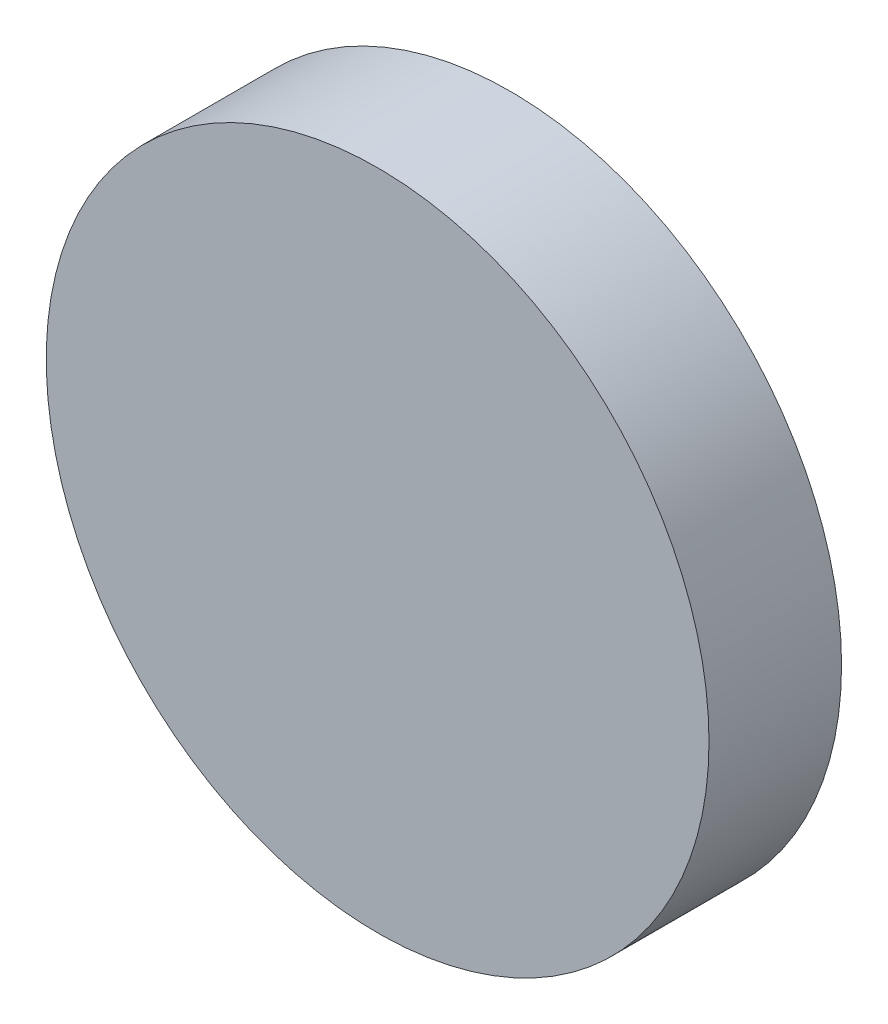
SolidWorks part; units mm, degrees
ref_plane "Front Plane" through (0, 0, 0) normal (0, 0, 1) x (1, 0, 0)
ref_plane "Top Plane" through (0, 0, 0) normal (0, 1, 0) x (1, 0, 0)
ref_plane "Right Plane" through (0, 0, 0) normal (1, 0, 0) x (0, 0, -1)
sketch "Sketch1" plane through (0, 0, 0) normal (0, 0, 1) x (1, 0, 0)
  circle A0 centre (0, 0) radius 50
  dimension "D1" = 100
extrude "Boss-Extrude1" add sketch "Sketch1" along normal blind 20
